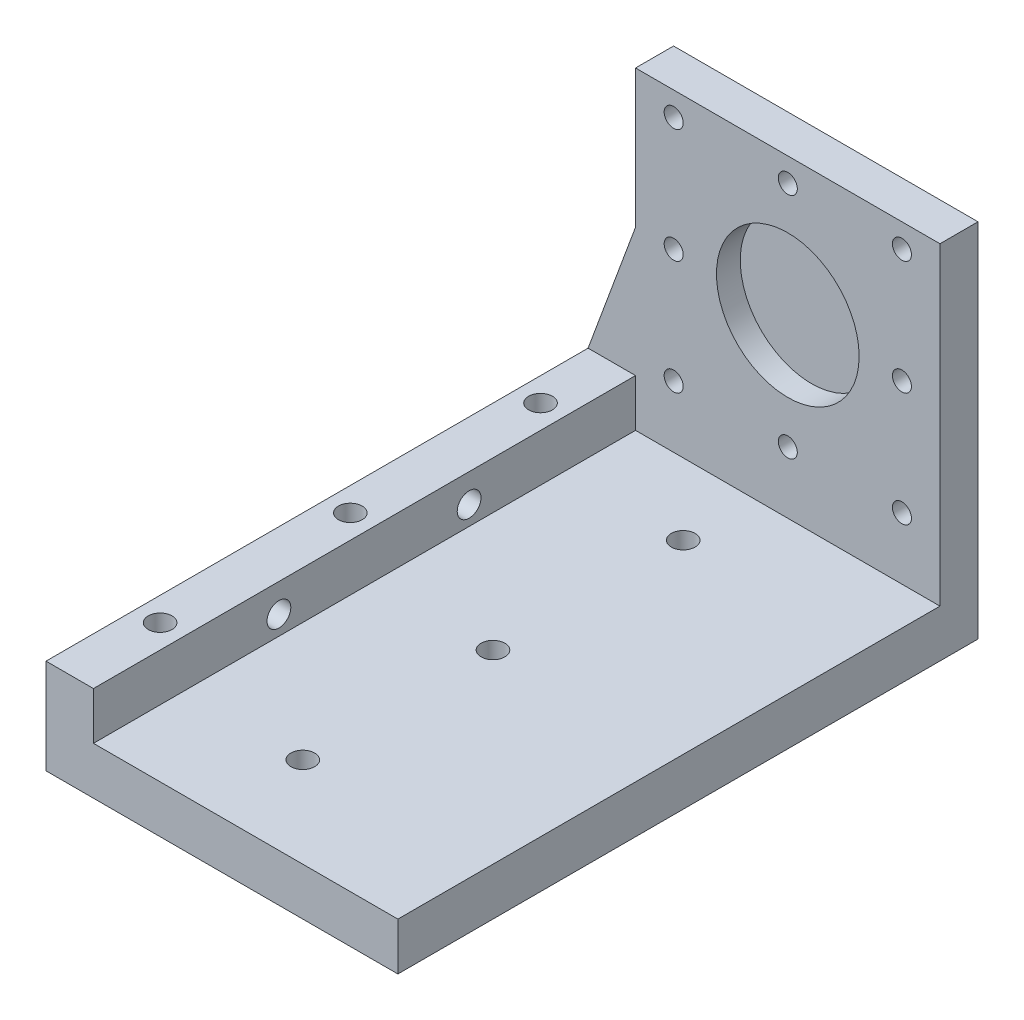
SolidWorks part; units mm, degrees
ref_plane "Front Plane" through (0, 0, 0) normal (0, 0, 1) x (1, 0, 0)
ref_plane "Top Plane" through (0, 0, 0) normal (0, 1, 0) x (1, 0, 0)
ref_plane "Right Plane" through (0, 0, 0) normal (1, 0, 0) x (0, 0, -1)
sketch "Sketch1" plane through (0, 0, 0) normal (0, 0, 1) x (1, 0, 0)
  line L0 (0, 0) -> (0, 24) construction
  line L1 (-29, -29) -> (29, -29)
  line L2 (-29, -29) -> (-29, 29)
  line L3 (-29, 29) -> (29, 29)
  line L4 (29, -29) -> (29, 29)
  line L5 (-29, -29) -> (29, 29) construction
  line L6 (-29, 29) -> (29, -29) construction
  line L7 (-29, 0) -> (29, 0) construction
  circle A1 centre (0, 24) radius 2
  circle A7 centre (-24, 24) radius 2
  circle A8 centre (24, 0) radius 2
  circle A9 centre (0, -24) radius 2
  circle A10 centre (-24, 0) radius 2
  circle A11 centre (24, -24) radius 2
  circle A12 centre (24, 24) radius 2
  circle A13 centre (-24, -24) radius 2
  point P0 (0, 0)
  point P21 (0, 0)
  point P22 (-3.4641, 2)
  dimension "D4" = 4
  dimension "D5" = 4
  dimension "D6" = 4
  dimension "D1" = 58
  dimension "D3" = 24
extrude "Boss-Extrude1" add sketch "Sketch1" along normal blind 8
sketch "Sketch13" plane through (0, 0, 8) normal (0, 0, 1) x (1, 0, 0)
  circle A0 centre (0, 0) radius 15
  point P0 (0, 0)
  dimension "D1" = 30
extrude "Cut-Extrude5" cut sketch "Sketch13" against normal blind 5
sketch "Sketch15" plane through (0, 0, 0) normal (0, 0, 1) x (1, 0, 0)
  line L1 (-29, -29) -> (29, -29)
  line L2 (-42, -29) -> (-42, 29)
  line L3 (-42, 29) -> (42, 29)
  line L4 (42, -29) -> (42, 29)
  line L5 (-42, -29) -> (42, 29) construction
  line L6 (-42, 29) -> (42, -29) construction
  line L7 (-29, -29) -> (29, -29)
  line L8 (-29, -29) -> (-29, 29)
  line L9 (-29, 29) -> (29, 29)
  line L10 (29, -29) -> (29, 29)
  line L11 (-29, -29) -> (29, 29) construction
  line L12 (-29, 29) -> (29, -29) construction
  line L13 (-29, -29) -> (29, -29)
  line L14 (-42, -29) -> (-42, -47)
  line L15 (-42, -47) -> (42, -47)
  line L16 (42, -29) -> (42, -47)
  point P0 (0, 0)
  point P5 (0, 0)
  dimension "D1" = 58
  dimension "D2" = 84
  dimension "D3" = 18
extrude "Boss-Extrude7" add sketch "Sketch15" along normal blind 8 contours L16 L4 L3 L10 L1 L8 L2 L14 L15
sketch "Sketch21" plane through (0, 0, 8) normal (0, 0, 1) x (1, 0, 0)
  line L1 (-42, -47) -> (42, -47)
  line L2 (-42, -47) -> (-42, -37)
  line L3 (-42, -37) -> (42, -37)
  line L4 (42, -47) -> (42, -37)
  dimension "D1" = 10
  dimension "D2" = 84
extrude "Boss-Extrude8" add sketch "Sketch21" along normal blind 114
sketch "Sketch22" plane through (0, 0, 8) normal (0, 0, 1) x (1, 0, 0)
  line L0 (0, -37) -> (0, -24) construction
  line L1 (-42, -37) -> (-32.02, -37)
  line L2 (-42, -37) -> (-42, -27.02)
  line L3 (-42, -27.02) -> (-32.02, -27.02)
  line L4 (-32.02, -37) -> (-32.02, -27.02)
  line L5 (42, -37) -> (-42, -37) construction
  line L6 (42, -27.02) -> (32.02, -27.02)
  line L7 (32.02, -37) -> (32.02, -27.02)
  line L8 (42, -37) -> (32.02, -37)
  line L9 (42, -37) -> (42, -27.02)
  dimension "D1" = 9.98
extrude "Boss-Extrude9" add sketch "Sketch22" along normal blind 114 contours L2 L1 L4 L3
sketch "Sketch29" plane through (-42, 0, 0) normal (-1, 0, 0) x (0, 0, 1)
  line L0 (8, -47) -> (33, -47) construction
  line L1 (122, -47) -> (0, -47) construction
  line L2 (63, -47) -> (73, -47) construction
  line L3 (113, -47) -> (93, -47) construction
  line L4 (13, -47) -> (33, -47) construction
  line L5 (53, -47) -> (63, -47) construction
  line L7 (33, -47) -> (33, -41)
  line L9 (53, -47) -> (53, -41)
  line L10 (13, -47) -> (33, -47)
  line L11 (13, -47) -> (13, -41)
  line L12 (13, -41) -> (33, -41)
  line L13 (33, -47) -> (33, -41)
  line L14 (53, -47) -> (73, -47)
  line L15 (53, -47) -> (53, -41)
  line L16 (53, -41) -> (73, -41)
  line L17 (73, -47) -> (73, -41)
  line L18 (113, -47) -> (93, -47)
  line L19 (113, -47) -> (113, -41)
  line L20 (113, -41) -> (93, -41)
  line L21 (93, -47) -> (93, -41)
  line L22 (33, -47) -> (13, -47) construction
  line L23 (93, -47) -> (113, -47) construction
  line L24 (73, -47) -> (53, -47) construction
  line M5 (0, -47) -> (122, -47)
  dimension "D1" = 55
  dimension "D2" = 50
  dimension "D3" = 100
  dimension "D4" = 20
  dimension "D5" = 6
  dimension "D6" = 20
  dimension "D7" = 6
  dimension "D8" = 20
  dimension "D9" = 6
  dimension "D10" = 20
extrude "Cut-Extrude6" cut sketch "Sketch29" against normal blind 40 contours L21 L19 L20 M5 | L17 L16 L9 M5 | L12 L11 L7 M5
sketch "Sketch30" plane through (0, 0, 122) normal (0, 0, 1) x (1, 0, 0)
  line L0 (42, 29) -> (32, 29) construction
  line L1 (42, 29) -> (-42, 29) construction
  line L2 (32, 29) -> (32, -47)
  line L3 (-42, -47) -> (42, -47) construction
  line L4 (32, -47) -> (42, -47)
  line L5 (42, -47) -> (42, 29)
  line L6 (42, 29) -> (32, 29)
  dimension "D1" = 10
extrude "Cut-Extrude7" cut sketch "Sketch30" against normal through all
sketch "Sketch31" plane through (0, -41, 0) normal (0, -1, 0) x (1, 0, 0)
  line L0 (-2, 103) -> (-7, 103) construction
  line L1 (-2, 113) -> (-2, 93) construction
  line L2 (-42, 83) -> (-19.087, 83) construction
  line L3 (-42, 93) -> (-42, 73) construction
  line L4 (-42, 43) -> (-19.087, 43) construction
  line L5 (-42, 53) -> (-42, 33) construction
  circle A0 centre (-7, 103) radius 2.5
  circle A1 centre (-7, 63) radius 2.5
  circle A2 centre (-7, 23) radius 2.5
  dimension "D2" = 5
  dimension "D1" = 5
extrude "Cut-Extrude8" cut sketch "Sketch31" against normal blind 4
sketch "Sketch34" plane through (-42, 0, 0) normal (-1, 0, 0) x (0, 0, 1)
  line L0 (83, -47) -> (83, -33) construction
  line L1 (93, -47) -> (73, -47) construction
  line L2 (43, -47) -> (43, -33) construction
  line L3 (53, -47) -> (33, -47) construction
  circle A0 centre (43, -33) radius 2.5
  circle A1 centre (83, -33) radius 2.5
  dimension "D3" = 5
  dimension "D4" = 5
  dimension "D1" = 14
  dimension "D2" = 14
extrude "Cut-Extrude9" cut sketch "Sketch34" against normal blind 10
sketch "Sketch36" plane through (0, -41, 0) normal (0, -1, 0) x (1, 0, 0)
  line L0 (-42, 103) -> (-37, 103) construction
  line L1 (-42, 113) -> (-42, 93) construction
  line L2 (-42, 63) -> (-37, 63) construction
  line L3 (-42, 53) -> (-42, 73) construction
  line L4 (-42, 23) -> (-37, 23) construction
  line L5 (-42, 13) -> (-42, 33) construction
  circle A0 centre (-37, 103) radius 2.5
  circle A1 centre (-37, 23) radius 2.5
  circle A2 centre (-37, 63) radius 2.5
  dimension "D2" = 5
  dimension "D5" = 5
  dimension "D6" = 5
  dimension "D1" = 5
  dimension "D3" = 5
  dimension "D4" = 5
extrude "Cut-Extrude10" cut sketch "Sketch36" against normal blind 20
sketch "Sketch37" plane through (0, 0, 8) normal (0, 0, 1) x (1, 0, 0)
  line L0 (-32.02, -27.02) -> (-32.02, 29) construction
  line L1 (32, 29) -> (-42, 29) construction
  line L2 (-42, -27.02) -> (-32.02, 0)
  line L4 (-32.02, 0) -> (-32.02, 29)
  line L5 (-32.02, 29) -> (-42, 29)
  line L6 (-42, 29) -> (-42, -27.02)
extrude "Cut-Extrude12" cut sketch "Sketch37" against normal blind 15
equation "\"ๅจภ\"=94"
